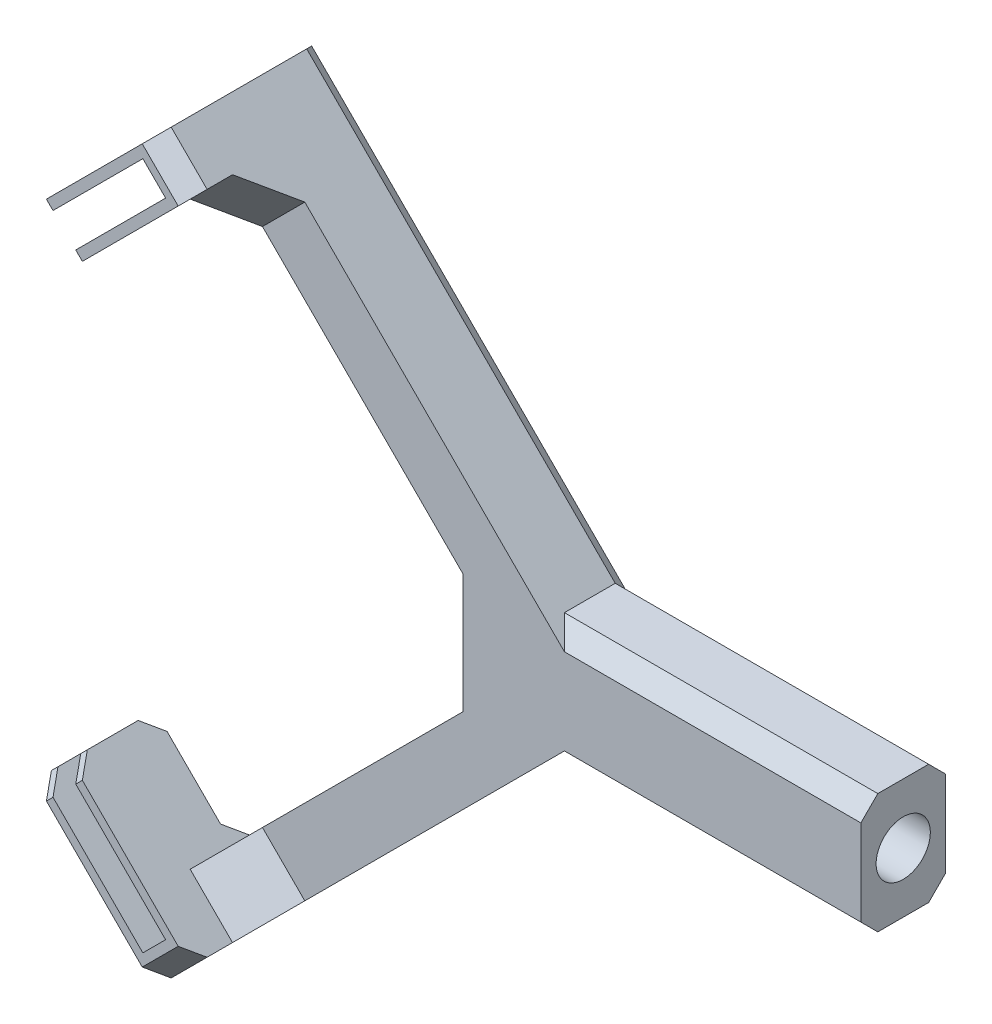
SolidWorks part; units mm, degrees
ref_plane "前视基准面" through (0, 0, 0) normal (0, 0, 1) x (1, 0, 0)
ref_plane "上视基准面" through (0, 0, 0) normal (0, 1, 0) x (1, 0, 0)
ref_plane "右视基准面" through (0, 0, 0) normal (1, 0, 0) x (0, 0, -1)
other "Configuration Table"
sketch "草图1" plane through (0, 0, 0) normal (0, 0, 1) x (1, 0, 0)
  line L0 (-10, 0) -> (33.5, 43.5)
  line L1 (33.5, 43.5) -> (38.5, 38.5)
  line L2 (38.5, 38.5) -> (0, 0)
  line L4 (0, 0) -> (43.2882, 0) construction
  line L5 (38.5, -38.5) -> (0, 0)
  line L6 (33.5, -43.5) -> (38.5, -38.5)
  line L7 (-10, 0) -> (33.5, -43.5)
  dimension "D1" = 90
  dimension "D2" = 10
  dimension "D3" = 38.5
extrude "凸台-拉伸1" add sketch "草图1" along normal mid plane 10
chamfer "倒角1" distance 10 angle 45 2 edges at (0, 0, 0) (-10, 0, 0)
sketch "草图2" plane through (-2.9289, 0, 0) normal (-1, 0, 0) x (0, 0, 1)
  circle A0 centre (0, 0) radius 2.1
  dimension "D1" = 4.2
extrude "切除-拉伸1" cut sketch "草图2" against normal through all and the other way through all
sketch "草图3" plane through (-2.9289, 0, 0) normal (-1, 0, 0) x (0, 0, 1)
  line L12 (5, -7.0711) -> (5, 7.0711)
  line L13 (5, 7.0711) -> (-5, 7.0711)
  line L14 (-5, 7.0711) -> (-5, -7.0711)
  line L15 (-5, -7.0711) -> (5, -7.0711)
  line L16 (5, -7.0711) -> (5, 7.0711)
  line L17 (5, 7.0711) -> (-5, 7.0711)
  line L18 (-5, 7.0711) -> (-5, -7.0711)
  line L19 (-5, -7.0711) -> (5, -7.0711)
  circle A0 centre (0, 0) radius 2.1 construction
  circle A1 centre (0, 0) radius 2.1
  dimension "D1" = 0
extrude "凸台-拉伸2" add sketch "草图3" along normal blind 37
sketch "草图4" plane through (38.5, 38.5, 0) normal (0.7071, 0.7071, 0) x (0, 0, -1)
  line L1 (-5, 7.0711) -> (-15, 7.0711)
  line L2 (-5, 7.0711) -> (-5, -12.9289)
  line L3 (-5, -12.9289) -> (-15, -12.9289)
  line L4 (-15, 7.0711) -> (-15, -12.9289)
  dimension "D1" = 20
  dimension "D2" = 10
extrude "凸台-拉伸3" add sketch "草图4" against normal blind 6
sketch "草图6" plane through (38.5, 38.5, 0) normal (0.7071, 0.7071, 0) x (0, 0, -1)
  line L0 (-5, -12.9289) -> (-5, 0) construction
  line L1 (-15, -12.9289) -> (-5, -12.9289)
  line L2 (-15, -12.9289) -> (-15, 19.0711)
  line L3 (-15, 19.0711) -> (-5, 19.0711)
  line L4 (-5, -12.9289) -> (-5, 19.0711)
  dimension "D1" = 32
extrude "凸台-拉伸5" add sketch "草图6" against normal blind 6
sketch "草图8" plane through (0, 0, 15) normal (0, 0, 1) x (1, 0, 0)
  line L0 (21.5499, 48.5205) -> (44.1773, 25.893)
  line L1 (20.7721, 47.7426) -> (25.0147, 51.9853) construction
  line L2 (43.3995, 25.1152) -> (47.6421, 29.3579) construction
  line L3 (44.1773, 25.893) -> (46.8643, 28.58)
  line L4 (46.8643, 28.58) -> (24.2369, 51.2075)
  line L5 (24.2369, 51.2075) -> (21.5499, 48.5205)
  line L6 (45.5208, 27.2365) -> (22.8934, 49.864) construction
  dimension "D1" = 3.8
extrude "切除-拉伸2" cut sketch "草图8" against normal blind 15
sketch "草图9" plane through (0, 0, 5) normal (0, 0, -1) x (-1, 0, 0)
  line L0 (-32.7222, 42.7222) -> (-24.2369, 51.2075) construction
  line L1 (-24.2369, 51.2075) -> (-25.0147, 51.9853) construction
  line L2 (-25.0147, 51.9853) -> (-33.5, 43.5) construction
  line L3 (-33.5, 43.5) -> (-32.7222, 42.7222) construction
  line L4 (-21.5499, 48.5205) -> (-30.0352, 40.0352) construction
  line L5 (-30.0352, 40.0352) -> (-29.2574, 39.2574) construction
  line L6 (-29.2574, 39.2574) -> (-20.7721, 47.7426) construction
  line L7 (-20.7721, 47.7426) -> (-21.5499, 48.5205) construction
  line L8 (-32.7222, 42.7222) -> (-24.2369, 51.2075)
  line L9 (-24.2369, 51.2075) -> (-25.0147, 51.9853)
  line L10 (-25.0147, 51.9853) -> (-33.5, 43.5)
  line L11 (-33.5, 43.5) -> (-32.7222, 42.7222)
  line L12 (-21.5499, 48.5205) -> (-30.0352, 40.0352)
  line L13 (-30.0352, 40.0352) -> (-29.2574, 39.2574)
  line L14 (-29.2574, 39.2574) -> (-20.7721, 47.7426)
  line L15 (-20.7721, 47.7426) -> (-21.5499, 48.5205)
extrude "切除-拉伸3" cut sketch "草图9" against normal through all
sketch "草图10" plane through (-5, 5, 0) normal (-0.7071, 0.7071, 0) x (0, 0, 1)
  line L0 (15, 49.5472) -> (15, 48.4472) construction
  line L1 (0, 53.3472) -> (15, 53.3472)
  line L2 (0, 53.3472) -> (0, 49.5472)
  line L3 (0, 49.5472) -> (15, 49.5472)
  line L4 (15, 53.3472) -> (15, 49.5472)
  line L5 (15, 49.5472) -> (0, 49.5472) construction
extrude "凸台-拉伸6" add sketch "草图10" against normal blind 3
chamfer "倒角2" distance 2 angle 45 8 edges at (15.2855, 25.2855, -5) (22.7855, 22.7855, -5) (38.1111, 38.1111, 5) (47.2532, 28.969, 5) (47.2532, 28.969, 15) (31.3787, 41.3787, 15) (43.7884, 25.5041, 5) (43.7884, 25.5041, 15)
mirror "镜向1" about plane through (0, 0, 0) normal (0, 1, 0) of "凸台-拉伸3", "凸台-拉伸5", "切除-拉伸2", "切除-拉伸3", "凸台-拉伸6"
chamfer "倒角3" distance 2 angle 45 9 edges at (38.1111, -38.1111, 5) (15.2855, -25.2855, -5) (43.7884, -25.5041, 5) (43.7884, -25.5041, 15) (34.6463, -34.6463, 5) (47.2532, -28.969, 5) (47.2532, -28.969, 15) (31.3787, -41.3787, 15) (22.7855, -22.7855, -5)
chamfer "倒角4" distance 5 angle 45 2 edges at (31.7574, -36.7574, 5) (31.7574, 36.7574, 5)
chamfer "倒角5" distance 2 angle 45 4 edges at (-20.0147, -7.0711, -5) (-20.0147, 7.0711, -5) (-21.4289, -7.0711, 5) (-21.4289, 7.0711, 5)
sketch "草图12" plane through (-39.9289, 0, 0) normal (-1, 0, 0) x (0, 0, 1)
  circle A0 centre (0, 0) radius 3.2
  dimension "D1" = 6.4
extrude "切除-拉伸4" cut sketch "草图12" against normal blind 38
sketch "草图13" plane through (7.0711, 0, 0) normal (1, 0, 0) x (0, 0, -1)
  line L1 (2.1073, -3.65) -> (4.2147, 0)
  line L2 (4.2147, 0) -> (2.1073, 3.65)
  line L3 (2.1073, 3.65) -> (-2.1073, 3.65)
  line L4 (-2.1073, 3.65) -> (-4.2147, 0)
  line L5 (-4.2147, 0) -> (-2.1073, -3.65)
  line L6 (-2.1073, -3.65) -> (2.1073, -3.65)
  circle A0 centre (0, 0) radius 3.65 construction
  dimension "D1" = 7.3
extrude "切除-拉伸5" cut sketch "草图13" against normal blind 4
mirror "镜向2" about plane through (-39.9289, 0, 0) normal (-1, 0, 0) of bodies 116
delete or keep bodies "实体-删除/保留 1" type delete bodies bodies 116
